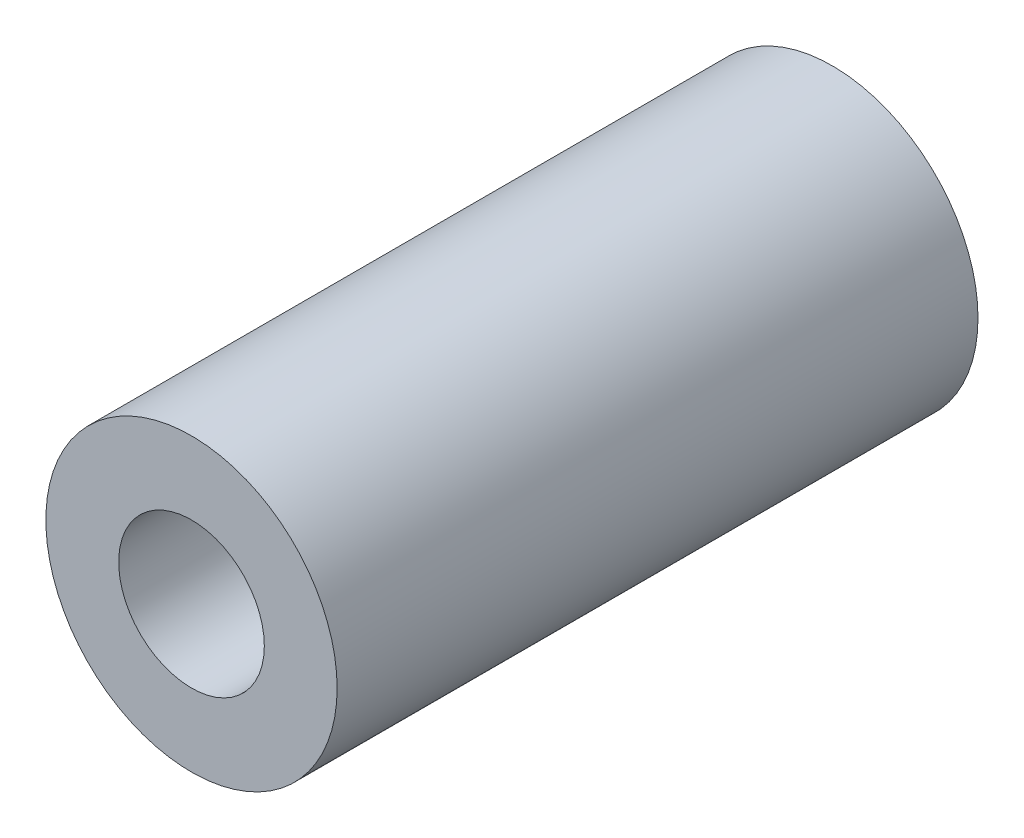
SolidWorks part; units mm, degrees
ref_plane "前视基准面" through (0, 0, 0) normal (0, 0, 1) x (1, 0, 0)
ref_plane "上视基准面" through (0, 0, 0) normal (0, 1, 0) x (1, 0, 0)
ref_plane "右视基准面" through (0, 0, 0) normal (1, 0, 0) x (0, 0, -1)
sketch "草图1" plane through (0, 0, 0) normal (0, 0, 1) x (1, 0, 0)
  circle A0 centre (0, 0) radius 5
  circle A1 centre (0, 0) radius 2.5
  dimension "D1" = 10
  dimension "D2" = 5
extrude "凸台-拉伸1" add sketch "草图1" along normal blind 22
